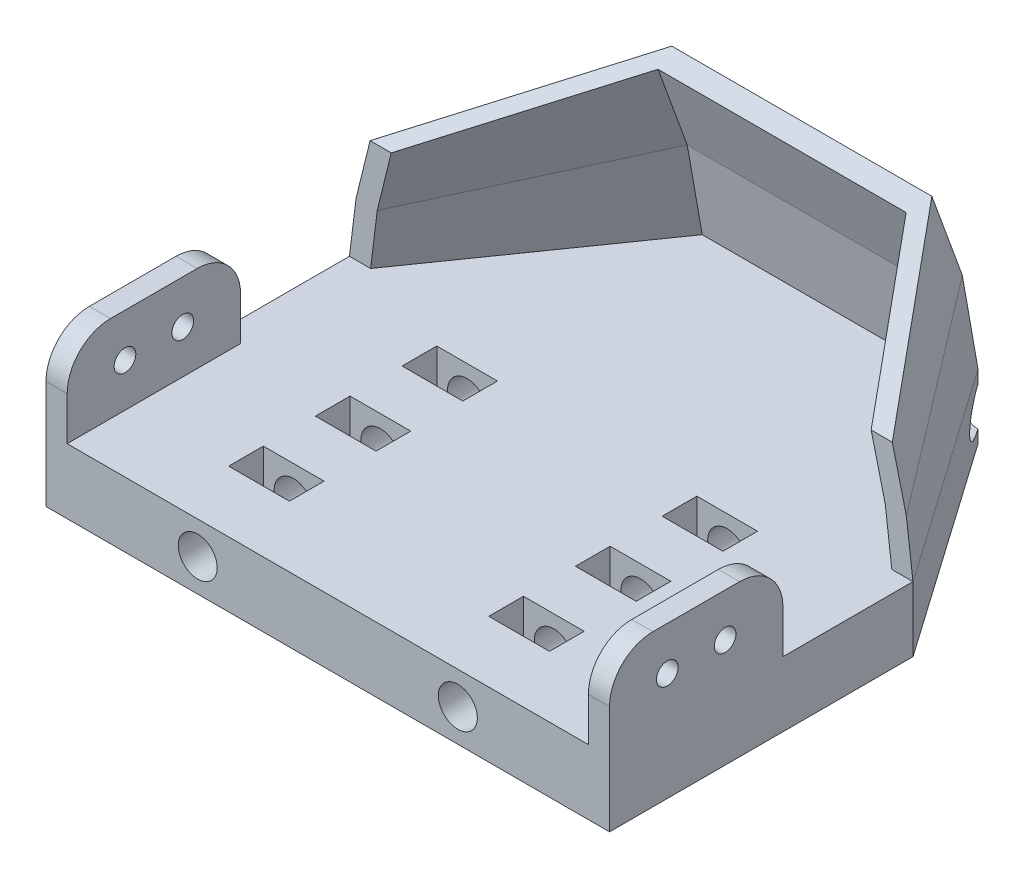
SolidWorks part; units mm, degrees
material "3.0205 (EN-AW 1200)"
ref_plane "前视基准面" through (0, 0, 0) normal (0, 0, 1) x (1, 0, 0)
ref_plane "上视基准面" through (0, 0, 0) normal (0, 1, 0) x (1, 0, 0)
ref_plane "右视基准面" through (0, 0, 0) normal (1, 0, 0) x (0, 0, -1)
sketch "草图1" plane through (0, 0, 0) normal (0, 1, 0) x (1, 0, 0)
  line L0 (-65, 0) -> (65, 0)
  line L1 (65, 0) -> (65, 70)
  line L2 (65, 70) -> (30, 120)
  line L3 (30, 120) -> (-30, 120)
  line L4 (-30, 120) -> (-65, 70)
  line L5 (-65, 70) -> (-65, 0)
  line L6 (0, -3014.6235) -> (0, 147716.5496) construction
  point P8 (0, 120)
  point P10 (0, 0)
  dimension "D1" = 130
  dimension "D2" = 60
  dimension "D3" = 120
  dimension "D4" = 70
extrude "凸台-拉伸1" add sketch "草图1" along normal blind 15
sketch "草图2" plane through (0, 15, 0) normal (0, 1, 0) x (1, 0, 0)
  line L0 (-65, 70) -> (-61.7231, 67.7062)
  line L1 (-61.7231, 67.7062) -> (-28.6174, 115)
  line L2 (-28.6174, 115) -> (28.6174, 115)
  line L3 (28.6174, 115) -> (61.7231, 67.7062)
  line L4 (61.7231, 67.7062) -> (65, 70)
  line L5 (65, 70) -> (30, 120)
  line L6 (30, 120) -> (-30, 120)
  line L7 (-30, 120) -> (-65, 70)
  dimension "D1" = 4
  dimension "D2" = 4
  dimension "D3" = 5
ref_plane "基准面4" through (0, 14.5477, 2.5652) normal (0, 0.9848, 0.1736) x (1, 0, 0)
sketch "草图3" plane through (0, 14.5477, 2.5652) normal (0, 0.9848, 0.1736) x (1, 0, 0)
  line L0 (-65, 71.5413) -> (-61.7231, 69.2823)
  line L1 (-61.7231, 69.2823) -> (-28.6174, 115.8576)
  line L2 (-28.6174, 115.8576) -> (28.6174, 115.8576)
  line L3 (28.6174, 115.8576) -> (61.7231, 69.2823)
  line L4 (61.7231, 69.2823) -> (65, 71.5413)
  line L5 (65, 71.5413) -> (30, 120.7817)
  line L6 (30, 120.7817) -> (-30, 120.7817)
  line L7 (-30, 120.7817) -> (-65, 71.5413)
loft "放样1" add profiles "草图2", "草图3"
sketch "草图9" plane through (0, 14.5477, 2.5652) normal (0, 0.9848, 0.1736) x (1, 0, 0)
  line L0 (-65, 71.5413) -> (-61.7231, 69.2823)
  line L1 (-61.7231, 69.2823) -> (-28.6174, 115.8576)
  line L2 (-28.6174, 115.8576) -> (28.6174, 115.8576)
  line L3 (28.6174, 115.8576) -> (61.7231, 69.2823)
  line L4 (61.7231, 69.2823) -> (65, 71.5413)
  line L5 (65, 71.5413) -> (30, 120.7817)
  line L6 (30, 120.7817) -> (-30, 120.7817)
  line L7 (-30, 120.7817) -> (-65, 71.5413)
ref_plane "基准面5" through (0, 13.2453, 4.8209) normal (0, 0.9397, 0.342) x (1, 0, 0)
sketch "草图10" plane through (0, 13.2453, 4.8209) normal (0, 0.9397, 0.342) x (1, 0, 0)
  line L0 (-65, 73.0195) -> (-61.7231, 70.7949)
  line L1 (-61.7231, 70.7949) -> (-28.6174, 116.6626)
  line L2 (-28.6174, 116.6626) -> (28.6174, 116.6626)
  line L3 (28.6174, 116.6626) -> (61.7231, 70.7949)
  line L4 (61.7231, 70.7949) -> (65, 73.0195)
  line L5 (65, 73.0195) -> (30, 121.5119)
  line L6 (30, 121.5119) -> (-30, 121.5119)
  line L7 (-30, 121.5119) -> (-65, 73.0195)
loft "放样2" add profiles "草图9", "草图10"
sketch "草图4" plane through (0, 0, 0) normal (0, 0, 1) x (1, 0, 0)
  line L0 (-65, 15) -> (-65, 68.1534)
  line L1 (-65, 68.1534) -> (65, 68.1534)
  line L2 (65, 68.1534) -> (65, 15)
  line L3 (65, 15) -> (-65, 15)
extrude "切除-拉伸1" cut sketch "草图4" against normal up to vertex (70 mm away) up to point (-65, 15, -70)
sketch "草图5" plane through (0, 15, 0) normal (0, 1, 0) x (1, 0, 0)
  line L9 (65, 0) -> (65, 40)
  line L10 (65, 0) -> (65, 70) construction
  line L11 (65, 40) -> (60.1174, 40)
  line L12 (60.1174, 40) -> (60.1174, 0)
  line L13 (-65, 0) -> (65, 0) construction
  line L14 (60.1174, 0) -> (65, 0)
  line L15 (-65, 0) -> (-65, 40)
  line L16 (-65, 70) -> (-65, 0) construction
  line L17 (-65, 40) -> (-60.1174, 40)
  line L18 (-60.1174, 40) -> (-60.1174, 0)
  line L19 (-60.1174, 0) -> (-65, 0)
  line L20 (-60.1174, 70) -> (-60.1174, 40) construction
  line L21 (60.1174, 40) -> (60.1174, 70) construction
  line L22 (-60.1174, 40) -> (60.1174, 40) construction
  dimension "D1" = 40
extrude "凸台-拉伸2" add sketch "草图5" along normal blind 20
sketch "草图6" plane through (-65, 0, 0) normal (-1, 0, 0) x (0, 0, 1)
  line L0 (-40, 25) -> (-26.6667, 25) construction
  line L3 (-40, 35) -> (-40, 15) construction
  line L4 (-26.6667, 25) -> (-13.3333, 25) construction
  line L5 (-13.3333, 25) -> (0, 25) construction
  line L6 (0, 35) -> (0, 0) construction
  circle A0 centre (-26.6667, 25) radius 2.5
  circle A1 centre (-13.3333, 25) radius 2.5
  dimension "D1" = 5
  dimension "D2" = 5
extrude "切除-拉伸2" cut sketch "草图6" against normal through all
fillet "圆角1" radius 10 4 edges at (-62.5587, 35, -40) (-62.5587, 35, 0) (62.5587, 35, -40) (62.5587, 35, 0)
sketch "草图7" plane through (0, 0, 0) normal (0, 0, 1) x (1, 0, 0)
  line L2 (-30, 7.5) -> (30, 7.5) construction
  line L5 (0, 0) -> (0, 7.5) construction
  line L6 (-65, 0) -> (65, 0) construction
  line L7 (0, 7.5) -> (0, 15) construction
  line L8 (-60.1174, 15) -> (60.1174, 15) construction
  circle A0 centre (-30, 7.5) radius 4.5
  circle A1 centre (30, 7.5) radius 4.5
  point P2 (0, 7.5)
  dimension "D1" = 9
  dimension "D2" = 9
  dimension "D3" = 60
extrude "切除-拉伸3" cut sketch "草图7" against normal through all
sketch "草图8" plane through (0, 15, 0) normal (0, 1, 0) x (1, 0, 0)
  line L0 (-37, 62.143) -> (-23, 62.143)
  line L1 (-23, 62.143) -> (-23, 54.143)
  line L2 (-23, 54.143) -> (-37, 54.143)
  line L3 (-37, 54.143) -> (-37, 62.143)
  line L4 (0, -1000) -> (0, 49000) construction
  line L5 (37, 54.143) -> (37, 62.143)
  line L6 (23, 54.143) -> (37, 54.143)
  line L7 (23, 62.143) -> (23, 54.143)
  line L8 (37, 62.143) -> (23, 62.143)
  line L9 (-34.5, 71.415) -> (-25.5, 71.415) construction
  line L10 (-34.5, 113.5714) -> (-34.5, 0) construction
  line L11 (-25.5, 0) -> (-25.5, 120) construction
  line L12 (-30, 71.415) -> (-30, 62.143) construction
  point P19 (-30, 62.143)
  dimension "D1" = 14
  dimension "D2" = 8
extrude "切除-拉伸4" cut sketch "草图8" against normal through all
pattern_linear "阵列(线性)1" count 3 spacing 20 along (0, 0, 1) of "切除-拉伸4"
